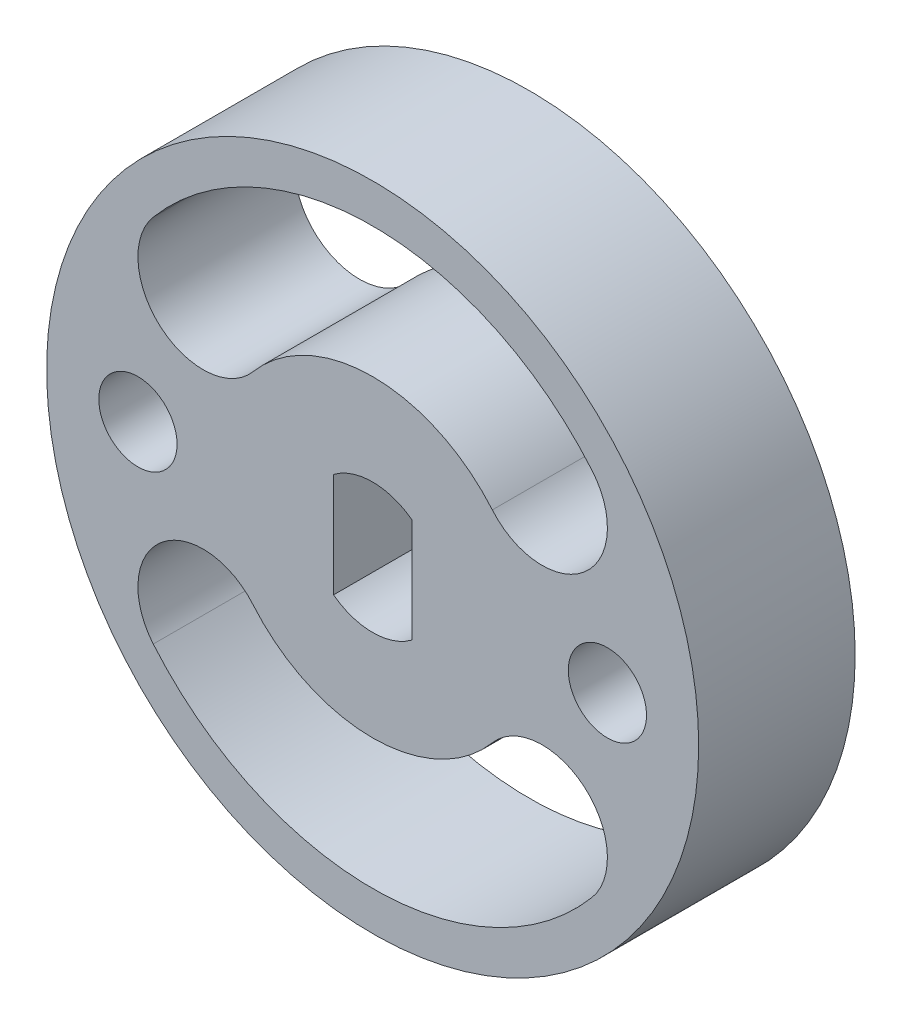
SolidWorks part; units mm, degrees
ref_plane "Front Plane" through (0, 0, 0) normal (0, 0, 1) x (1, 0, 0)
ref_plane "Top Plane" through (0, 0, 0) normal (0, 1, 0) x (1, 0, 0)
ref_plane "Right Plane" through (0, 0, 0) normal (1, 0, 0) x (0, 0, -1)
sketch "Sketch1" plane through (0, 0, 0) normal (0, 0, 1) x (1, 0, 0)
  line L0 (1.5, 2) -> (1.5, 0)
  line L1 (1.5, 0) -> (7.5, 0)
  line L2 (10.5, 0) -> (12.5, 0)
  line L3 (0, 12.5) -> (0, 2.5)
  arc A0 (0, 2.5) -> (1.5, 2) centre (0, 0) cw
  arc A1 (7.5, 0) -> (10.5, 0) centre (9, 0) cw
  arc A2 (12.5, 0) -> (0, 12.5) centre (0, 0) ccw
  point P11 (14.6665, 0)
  dimension "D1" = 1.5
  dimension "D2" = 2.5
  dimension "D4" = 12.5
  dimension "D5" = 12.5
  dimension "D3" = 9
  dimension "D6" = 1.5
extrude "Boss-Extrude1" add sketch "Sketch1" along normal blind 6
mirror "Mirror4" about plane through (0, 12.5, 6) normal (1, 0, 0) of bodies 101
sketch "Sketch2" plane through (0, 0, 6) normal (0, 0, 1) x (1, 0, 0)
  line L0 (-6.5, 5.4772) -> (6.5, 5.4772) construction
  arc A0 (-6.5, 5.4772) -> (6.5, 5.4772) centre (0, 0) cw construction
  arc A1 (8.4118, 7.0882) -> (-8.4118, 7.0882) centre (0, 0) ccw
  arc A2 (4.5882, 3.8663) -> (-4.5882, 3.8663) centre (0, 0) ccw
  arc A3 (4.5882, 3.8663) -> (8.4118, 7.0882) centre (6.5, 5.4772) ccw
  arc A4 (-8.4118, 7.0882) -> (-4.5882, 3.8663) centre (-6.5, 5.4772) ccw
  point P5 (0, 8.5)
  point P13 (0, 6)
  dimension "D2" = 13
  dimension "D1" = 8.5
  dimension "D3" = 6
extrude "Cut-Extrude1" cut sketch "Sketch2" against normal up to surface (6 mm away) up to face at (0, 2, 0)
mirror "Mirror5" about plane through (-1.5, 0, 6) normal (0, 1, 0) of bodies 109 106
